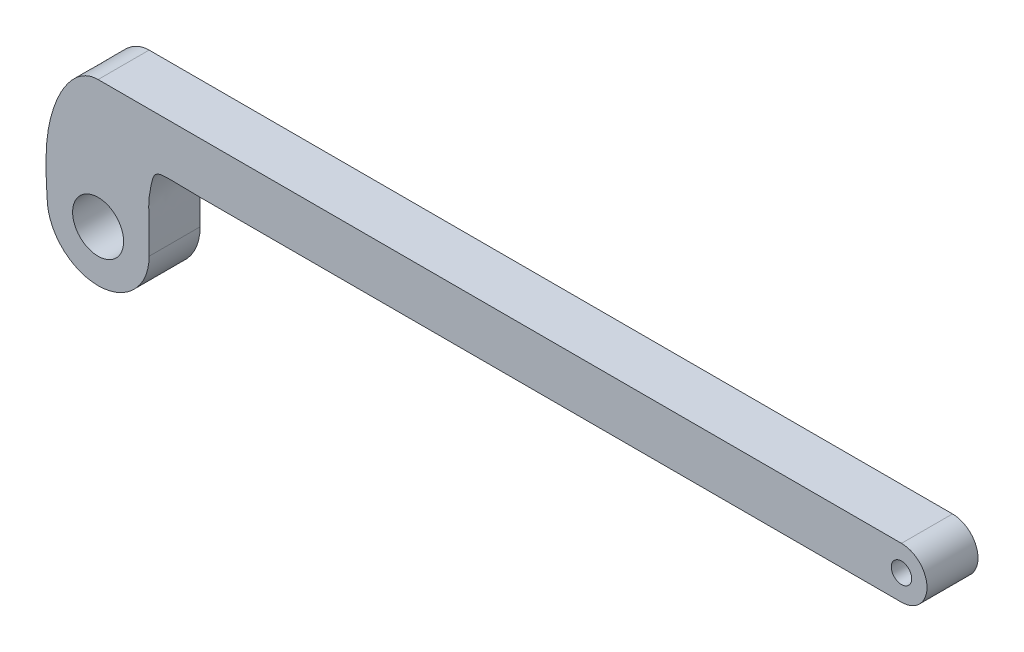
SolidWorks part; units mm, degrees
ref_plane "Front Plane" through (0, 0, 0) normal (1, 0, 0) x (0, 1, 0)
ref_plane "Top Plane" through (0, 0, 0) normal (0, 0, 1) x (0, 1, 0)
ref_plane "Right Plane" through (0, 0, 0) normal (0, 1, 0) x (-1, 0, 0)
sketch "Sketch1" plane through (0, 0, 0) normal (0, 0, 1) x (0, 1, 0)
  line L3 (25, 0) -> (25, -157.485)
  line L4 (15, -20) -> (15, -157.485)
  line L5 (10, 10) -> (10, -10) construction
  circle A0 centre (0, 0) radius 10 construction
  circle A1 centre (20, -157.485) radius 2
  arc A2 (15, -157.485) -> (25, -157.485) centre (20, -157.485) ccw
  circle A5 centre (0, 0) radius 5
  arc A6 (0, 10) -> (0, -10) centre (0, 0) ccw
  spline S0 degree 3 poles (0, 10) (0.6811, 10) (14.2397, 11.4058) (25, 4.9314) (25, 0) knots 0 0 0 0 0.356789 1 1 1 1
  spline S1 degree 3 poles (0, -10) (6.7902, -10) (8.9866, -9.7761) (16.1248, -11.0749) (15, -11.1995) (15, -20) knots 0 0 0 0 0.182752 0.282752 1 1 1 1
  point P23 (10, 0)
  dimension "D1" = 10
  dimension "D6" = 5
  dimension "D2" = 157.485
  dimension "D3" = 10
  dimension "D4" = 20
  dimension "D5" = 10
extrude "Boss-Extrude1" add sketch "Sketch1" along normal blind 10
equation "\"D1@Sketch1\"=\"BearingDiameter\""
equation "\"ThighLength\"= 200"
equation "\"BearingBore\"=4"
equation "\"MinShinWidth\"= 20"
equation "\"HipBore\"=27"
equation "\"ShinThickness\"=10"
equation "\"ThighThickness\"=20"
equation "\"MaxBending\"=135"
equation "\"MaxStretchingAngle\"= 140"
equation "\"ThighJointDistance\"=157.485"
equation "\"PivotDistance\"=30"
equation "\"ShinLength\"=120"
equation "\"BearingDiameter\"= 10"
equation "\"D2@Sketch1\"=\"ThighJointDistance\""
